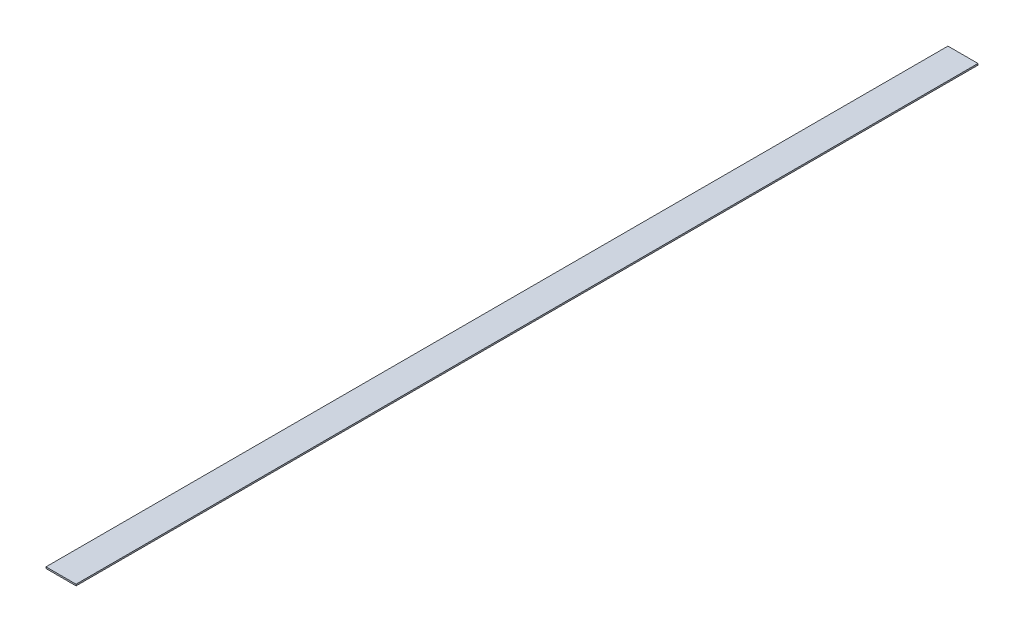
SolidWorks part; units mm, degrees
material "Thornel VCB-20 Carbon Cloth"
ref_plane "Front Plane" through (0, 0, 0) normal (0, 0, 1) x (1, 0, 0)
ref_plane "Top Plane" through (0, 0, 0) normal (0, 1, 0) x (1, 0, 0)
ref_plane "Right Plane" through (0, 0, 0) normal (1, 0, 0) x (0, 0, -1)
sketch "Sketch1" plane through (0, 0, 0) normal (0, 1, 0) x (1, 0, 0)
  line L1 (-2, 60) -> (2, 60)
  line L2 (-2, 60) -> (-2, -60)
  line L3 (-2, -60) -> (2, -60)
  line L4 (2, 60) -> (2, -60)
  line L5 (-2, 60) -> (2, -60) construction
  line L6 (-2, -60) -> (2, 60) construction
  point P0 (0, 0)
  dimension "D1" = 4
  dimension "D2" = 120
extrude "Boss-Extrude1" add sketch "Sketch1" along normal blind 0.2
